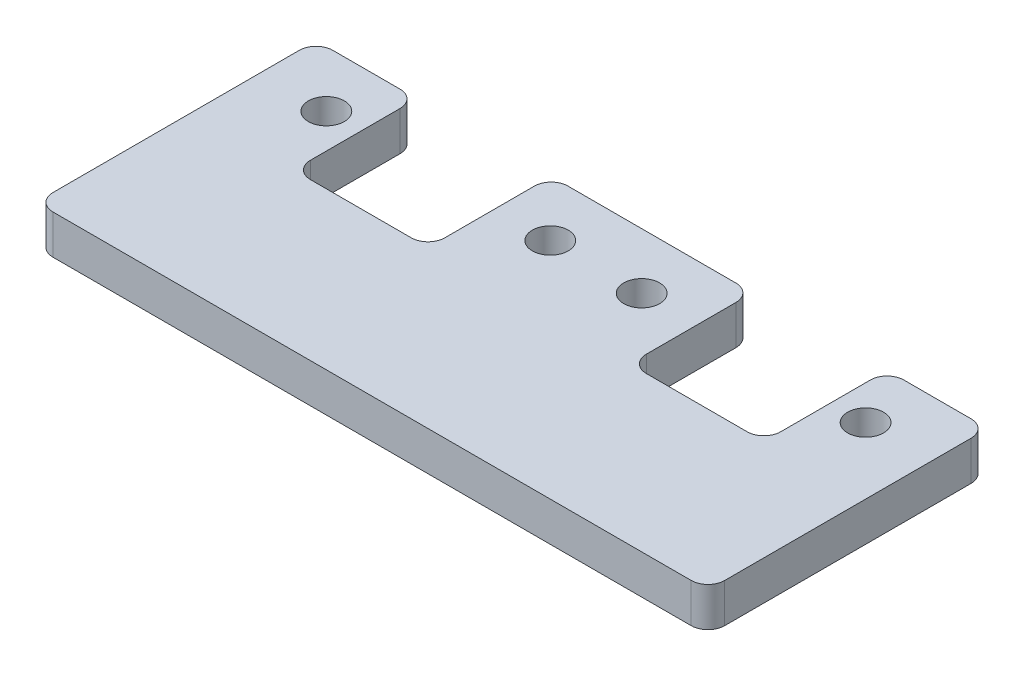
SolidWorks part; units mm, degrees
ref_plane "Front Plane" through (0, 0, 0) normal (0, 0, 1) x (1, 0, 0)
ref_plane "Top Plane" through (0, 0, 0) normal (0, 1, 0) x (1, 0, 0)
ref_plane "Right Plane" through (0, 0, 0) normal (1, 0, 0) x (0, 0, -1)
sketch "Sketch1" plane through (0, 0, 0) normal (0, 1, 0) x (1, 0, 0)
  line L0 (-21, 12.5) -> (-21, 1.5)
  line L1 (-30, -12.5) -> (30, -12.5)
  line L2 (-30, -12.5) -> (-30, 12.5)
  line L3 (-30, 12.5) -> (-21, 12.5)
  line L4 (30, -12.5) -> (30, 12.5)
  line L5 (-30, -12.5) -> (30, 12.5) construction
  line L6 (-30, 12.5) -> (30, -12.5) construction
  line L7 (-21, 1.5) -> (-9, 1.5)
  line L8 (-9, 1.5) -> (-9, 12.5)
  line L9 (9, 12.5) -> (9, 1.5)
  line L10 (9, 1.5) -> (21, 1.5)
  line L11 (21, 1.5) -> (21, 12.5)
  line L12 (-21, 12.5) -> (-9, 12.5) construction
  line L13 (-9, 12.5) -> (9, 12.5)
  line L14 (9, 12.5) -> (21, 12.5) construction
  line L15 (21, 12.5) -> (30, 12.5)
  point P0 (0, 0)
  dimension "D1" = 60
  dimension "D2" = 25
  dimension "D3" = 9
  dimension "D4" = 11
  dimension "D5" = 18
extrude "Boss-Extrude1" add sketch "Sketch1" along normal blind 3.5
sketch "Sketch2" plane through (0, 3.5, 0) normal (0, 1, 0) x (1, 0, 0)
  line L0 (-24.08, 7.5) -> (-4.08, 7.5) construction
  line L1 (-4.08, 7.5) -> (4.08, 7.5) construction
  line L2 (4.08, 7.5) -> (24.08, 7.5) construction
  line L4 (9, 12.5) -> (-9, 12.5) construction
  point P2 (0, 7.5)
  point P7 (-24.08, 7.5)
  point P8 (-4.08, 7.5)
  point P9 (4.08, 7.5)
  point P10 (24.08, 7.5)
  dimension "D1" = 20
  dimension "D2" = 8.16
  dimension "D3" = 5
hole_wizard "#2 Clearance Hole1" positions "Sketch2" profile "Sketch3" hole size "#2" standard "ANSI Inch" end condition through all
sketch "Sketch3" plane through (24.08, 3.5, -7.5) normal (1, 0, 0) x (0, 0, 1)
  line L0 (0, 0) -> (0, 3.5)
  line L1 (0, 3.5) -> (1.6065, 3.5)
  line L2 (1.6065, 3.5) -> (1.6065, 0)
  line L5 (1.6065, 0) -> (0, 0)
  line L11 (0, -6.35) -> (0, 107.95) construction
  dimension "Thru Hole Dia." = 3.2131
  dimension "Thru Hole Depth" = 3.5
fillet "Fillet1" radius 1.5 12 edges at (30, 1.75, -12.5) (30, 1.75, 12.5) (-30, 1.75, -12.5) (-21, 1.75, -12.5) (-21, 1.75, -1.5) (-9, 1.75, -1.5) (-9, 1.75, -12.5) (9, 1.75, -12.5) (9, 1.75, -1.5) (21, 1.75, -1.5) (21, 1.75, -12.5) (-30, 1.75, 12.5)
